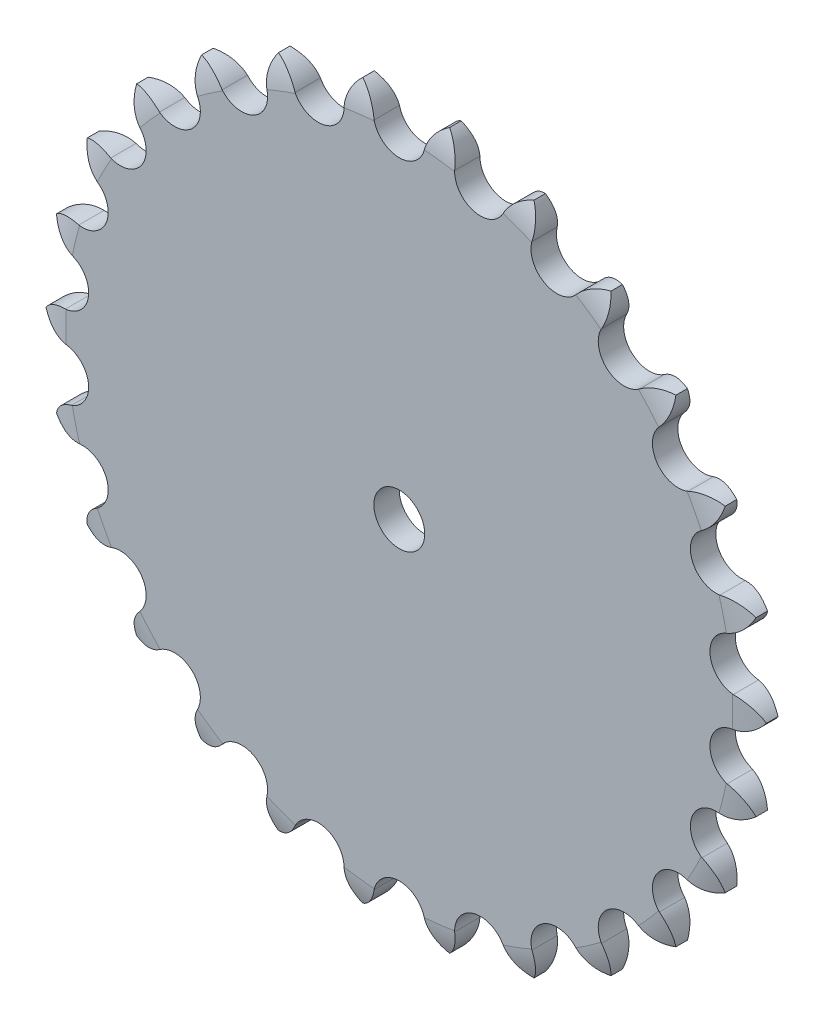
SolidWorks part; units mm, degrees
material "Plain Carbon Steel"
ref_plane "Front Plane" through (0, 0, 0) normal (0, 0, 1) x (1, 0, 0)
ref_plane "Top Plane" through (0, 0, 0) normal (0, 1, 0) x (1, 0, 0)
ref_plane "Right Plane" through (0, 0, 0) normal (1, 0, 0) x (0, 0, -1)
sketch "Sketch2" plane through (0, 0, 0) normal (0, 0, 1) x (1, 0, 0)
  line L0 (0, 0) -> (0, 79.9625) construction
  line L1 (0, 0) -> (9.6643, 51.1653) construction
  circle A0 centre (0, 0) radius 56.769 construction
  circle A1 centre (0, 0) radius 53.34 construction
  circle A2 centre (0, 0) radius 52.07 construction
  arc A3 (-3.9649, 52.4478) -> (3.9649, 52.4478) centre (0, 53.34) ccw
  arc A4 (-6.9555, 56.3413) -> (-3.9649, 52.4478) centre (-9.6643, 51.1653) cw
  arc A5 (6.9555, 56.3413) -> (3.9649, 52.4478) centre (9.6643, 51.1653) ccw
  arc A6 (6.73, 56.3687) -> (8.7019, 51.8726) centre (2.8611, 51.9913) cw
  arc A7 (8.7019, 51.8726) -> (16.4012, 49.9749) centre (12.7651, 51.79) ccw
  arc A8 (20.2367, 53.0396) -> (16.4012, 49.9749) centre (21.6282, 47.3657) ccw
  arc A9 (20.0243, 53.1201) -> (20.863, 48.2828) centre (15.2203, 49.7958) cw
  arc A10 (20.863, 48.2828) -> (27.8844, 44.5977) centre (24.7883, 47.2302) ccw
  arc A11 (32.3419, 46.6554) -> (27.8844, 44.5977) centre (32.335, 40.8134) ccw
  arc A12 (32.1549, 46.7844) -> (31.8116, 41.8869) centre (26.695, 44.7064) cw
  arc A13 (31.8116, 41.8869) -> (37.7471, 36.6286) centre (35.371, 39.9256) ccw
  arc A14 (42.5674, 37.5597) -> (37.7471, 36.6286) centre (41.1627, 31.8891) ccw
  arc A15 (42.4168, 37.7298) -> (40.9114, 33.0568) centre (36.6182, 37.0188) cw
  arc A16 (40.9114, 33.0568) -> (45.416, 26.5307) centre (43.898, 30.3006) ccw
  arc A17 (50.3191, 26.2812) -> (45.416, 26.5307) centre (47.5982, 21.1116) ccw
  arc A18 (50.2136, 26.4824) -> (47.6336, 22.3055) centre (44.4133, 27.1798) cw
  arc A19 (47.6336, 22.3055) -> (50.4455, 14.891) centre (49.8738, 18.9146) ccw
  arc A20 (55.1465, 13.4754) -> (50.4455, 14.891) centre (51.2674, 9.1071) ccw
  arc A21 (55.0921, 13.696) -> (51.5875, 10.2578) centre (49.6273, 15.7612) cw
  arc A22 (51.5875, 10.2578) -> (52.5433, 2.3859) centre (52.9511, 6.4294) ccw
  arc A23 (56.7689, -0.1136) -> (52.5433, 2.3859) centre (51.9571, -3.4266) ccw
  arc A24 (56.7689, 0.1136) -> (52.5433, -2.3859) centre (51.9571, 3.4266) cw
  arc A25 (52.5433, -2.3859) -> (51.5875, -10.2578) centre (52.9511, -6.4294) ccw
  arc A26 (55.0921, -13.696) -> (51.5875, -10.2578) centre (49.6273, -15.7612) ccw
  arc A27 (55.1465, -13.4754) -> (50.4455, -14.891) centre (51.2674, -9.1071) cw
  arc A28 (50.4455, -14.891) -> (47.6336, -22.3055) centre (49.8738, -18.9146) ccw
  arc A29 (50.2136, -26.4824) -> (47.6336, -22.3055) centre (44.4133, -27.1798) ccw
  arc A30 (50.3191, -26.2812) -> (45.416, -26.5307) centre (47.5982, -21.1116) cw
  arc A31 (45.416, -26.5307) -> (40.9114, -33.0568) centre (43.898, -30.3006) ccw
  arc A32 (42.4168, -37.7298) -> (40.9114, -33.0568) centre (36.6182, -37.0188) ccw
  arc A33 (42.5674, -37.5597) -> (37.7471, -36.6286) centre (41.1627, -31.8891) cw
  arc A34 (37.7471, -36.6286) -> (31.8116, -41.8869) centre (35.371, -39.9256) ccw
  arc A35 (32.1549, -46.7844) -> (31.8116, -41.8869) centre (26.695, -44.7064) ccw
  arc A36 (32.3419, -46.6554) -> (27.8844, -44.5977) centre (32.335, -40.8134) cw
  arc A37 (27.8844, -44.5977) -> (20.863, -48.2828) centre (24.7883, -47.2302) ccw
  arc A38 (20.0243, -53.1201) -> (20.863, -48.2828) centre (15.2203, -49.7958) ccw
  arc A39 (20.2367, -53.0396) -> (16.4012, -49.9749) centre (21.6282, -47.3657) cw
  arc A40 (16.4012, -49.9749) -> (8.7019, -51.8726) centre (12.7651, -51.79) ccw
  arc A41 (6.73, -56.3687) -> (8.7019, -51.8726) centre (2.8611, -51.9913) ccw
  arc A42 (6.9555, -56.3413) -> (3.9649, -52.4478) centre (9.6643, -51.1653) cw
  arc A43 (3.9649, -52.4478) -> (-3.9649, -52.4478) centre (0, -53.34) ccw
  arc A44 (-6.9555, -56.3413) -> (-3.9649, -52.4478) centre (-9.6643, -51.1653) ccw
  arc A45 (-6.73, -56.3687) -> (-8.7019, -51.8726) centre (-2.8611, -51.9913) cw
  arc A46 (-8.7019, -51.8726) -> (-16.4012, -49.9749) centre (-12.7651, -51.79) ccw
  arc A47 (-20.2367, -53.0396) -> (-16.4012, -49.9749) centre (-21.6282, -47.3657) ccw
  arc A48 (-20.0243, -53.1201) -> (-20.863, -48.2828) centre (-15.2203, -49.7958) cw
  arc A49 (-20.863, -48.2828) -> (-27.8844, -44.5977) centre (-24.7883, -47.2302) ccw
  arc A50 (-32.3419, -46.6554) -> (-27.8844, -44.5977) centre (-32.335, -40.8134) ccw
  arc A51 (-32.1549, -46.7844) -> (-31.8116, -41.8869) centre (-26.695, -44.7064) cw
  arc A52 (-31.8116, -41.8869) -> (-37.7471, -36.6286) centre (-35.371, -39.9256) ccw
  arc A53 (-42.5674, -37.5597) -> (-37.7471, -36.6286) centre (-41.1627, -31.8891) ccw
  arc A54 (-42.4168, -37.7298) -> (-40.9114, -33.0568) centre (-36.6182, -37.0188) cw
  arc A55 (-40.9114, -33.0568) -> (-45.416, -26.5307) centre (-43.898, -30.3006) ccw
  arc A56 (-50.3191, -26.2812) -> (-45.416, -26.5307) centre (-47.5982, -21.1116) ccw
  arc A57 (-50.2136, -26.4824) -> (-47.6336, -22.3055) centre (-44.4133, -27.1798) cw
  arc A58 (-47.6336, -22.3055) -> (-50.4455, -14.891) centre (-49.8738, -18.9146) ccw
  arc A59 (-55.1465, -13.4754) -> (-50.4455, -14.891) centre (-51.2674, -9.1071) ccw
  arc A60 (-55.0921, -13.696) -> (-51.5875, -10.2578) centre (-49.6273, -15.7612) cw
  arc A61 (-51.5875, -10.2578) -> (-52.5433, -2.3859) centre (-52.9511, -6.4294) ccw
  arc A62 (-56.7689, 0.1136) -> (-52.5433, -2.3859) centre (-51.9571, 3.4266) ccw
  arc A63 (-56.7689, -0.1136) -> (-52.5433, 2.3859) centre (-51.9571, -3.4266) cw
  arc A64 (-52.5433, 2.3859) -> (-51.5875, 10.2578) centre (-52.9511, 6.4294) ccw
  arc A65 (-55.0921, 13.696) -> (-51.5875, 10.2578) centre (-49.6273, 15.7612) ccw
  arc A66 (-55.1465, 13.4754) -> (-50.4455, 14.891) centre (-51.2674, 9.1071) cw
  arc A67 (-50.4455, 14.891) -> (-47.6336, 22.3055) centre (-49.8738, 18.9146) ccw
  arc A68 (-50.2136, 26.4824) -> (-47.6336, 22.3055) centre (-44.4133, 27.1798) ccw
  arc A69 (-50.3191, 26.2812) -> (-45.416, 26.5307) centre (-47.5982, 21.1116) cw
  arc A70 (-45.416, 26.5307) -> (-40.9114, 33.0568) centre (-43.898, 30.3006) ccw
  arc A71 (-42.4168, 37.7298) -> (-40.9114, 33.0568) centre (-36.6182, 37.0188) ccw
  arc A72 (-42.5674, 37.5597) -> (-37.7471, 36.6286) centre (-41.1627, 31.8891) cw
  arc A73 (-37.7471, 36.6286) -> (-31.8116, 41.8869) centre (-35.371, 39.9256) ccw
  arc A74 (-32.1549, 46.7844) -> (-31.8116, 41.8869) centre (-26.695, 44.7064) ccw
  arc A75 (-32.3419, 46.6554) -> (-27.8844, 44.5977) centre (-32.335, 40.8134) cw
  arc A76 (-27.8844, 44.5977) -> (-20.863, 48.2828) centre (-24.7883, 47.2302) ccw
  arc A77 (-20.0243, 53.1201) -> (-20.863, 48.2828) centre (-15.2203, 49.7958) ccw
  arc A78 (-20.2367, 53.0396) -> (-16.4012, 49.9749) centre (-21.6282, 47.3657) cw
  arc A79 (-16.4012, 49.9749) -> (-8.7019, 51.8726) centre (-12.7651, 51.79) ccw
  arc A80 (-6.73, 56.3687) -> (-8.7019, 51.8726) centre (-2.8611, 51.9913) ccw
  circle A81 centre (0, 0) radius 4
  point P8 (0, 0)
  point P191 (0, 0)
  dimension "D1" = 113.538
  dimension "D2" = 106.68
  dimension "D3" = 104.14
  dimension "D4" = 8.128
  dimension "D5" = 5.842
  dimension "D7" = 8
  dimension "D6" = 26
extrude "Boss-Extrude1" add sketch "Sketch2" along normal blind 4 contours A4 A80 A79 A78 A77 A76 A75 A74 A73 A72 A71 A70 A69 A68 A67 A66 A65 A64 A63 A62 A61 A60 A59 A58 A57 A56 A55 A54 A53 A52 A51 A50 A49 A48 A47 A46 A45 A44 A43 A42 A41 A40 A39 A38 A37 A36 A35 A34 A33 A32 A31
sketch "Sketch3" plane through (0, 0, 0) normal (1, 0, 0) x (0, 0, -1)
  line L0 (0, 0) -> (-75.6862, 0) construction
  line L1 (-4, 33.0568) -> (-4, 26.2366) construction
  line L2 (-4, 28.575) -> (-23.05, 28.575)
  line L3 (-4, 28.575) -> (-4, 19.05)
  line L4 (-4, 19.05) -> (-23.05, 19.05)
  line L5 (-23.05, 28.575) -> (-23.05, 19.05)
  dimension "D1" = 19.05
  dimension "D2" = 19.05
  dimension "D3" = 28.575
sketch "Sketch7" plane through (0, 0, 0) normal (1, 0, 0) x (0, 0, -1)
  line L0 (-2, 56.2754) -> (-2, 49.8539) construction
  line L1 (-4, 56.2754) -> (0, 56.2754) construction
  line L2 (-2.4125, 56.2754) -> (-2.4125, 50.2263) construction
  line L3 (-4, 53.0048) -> (-4, 48.2828) construction
  line L4 (-4, 50.419) -> (-7.7746, 50.419)
  line L5 (-7.7746, 50.419) -> (-7.7746, 56.896)
  line L6 (-7.7746, 56.896) -> (-2.8088, 56.896)
  line L7 (-1.5875, 56.2754) -> (-1.5875, 50.2263) construction
  line L8 (3.7746, 56.896) -> (-1.1912, 56.896)
  line L9 (3.7746, 50.419) -> (3.7746, 56.896)
  line L10 (0, 50.419) -> (3.7746, 50.419)
  line L11 (0, 0) -> (92.826, 0) construction
  arc A0 (-2.8088, 56.896) -> (-4, 50.419) centre (8.659, 51.4389) ccw
  arc A1 (-1.1912, 56.896) -> (0, 50.419) centre (-12.659, 51.4389) cw
  dimension "D2" = 12.7
  dimension "D1" = 1.5875
  dimension "D3" = 50.419
  dimension "D4" = 56.896
revolve "Cut-Revolve1" cut sketch "Sketch7" angle 360 about L11
ref_plane "Plane1" through (0, 0, 2) normal (0, 0, 1) x (1, 0, 0)
